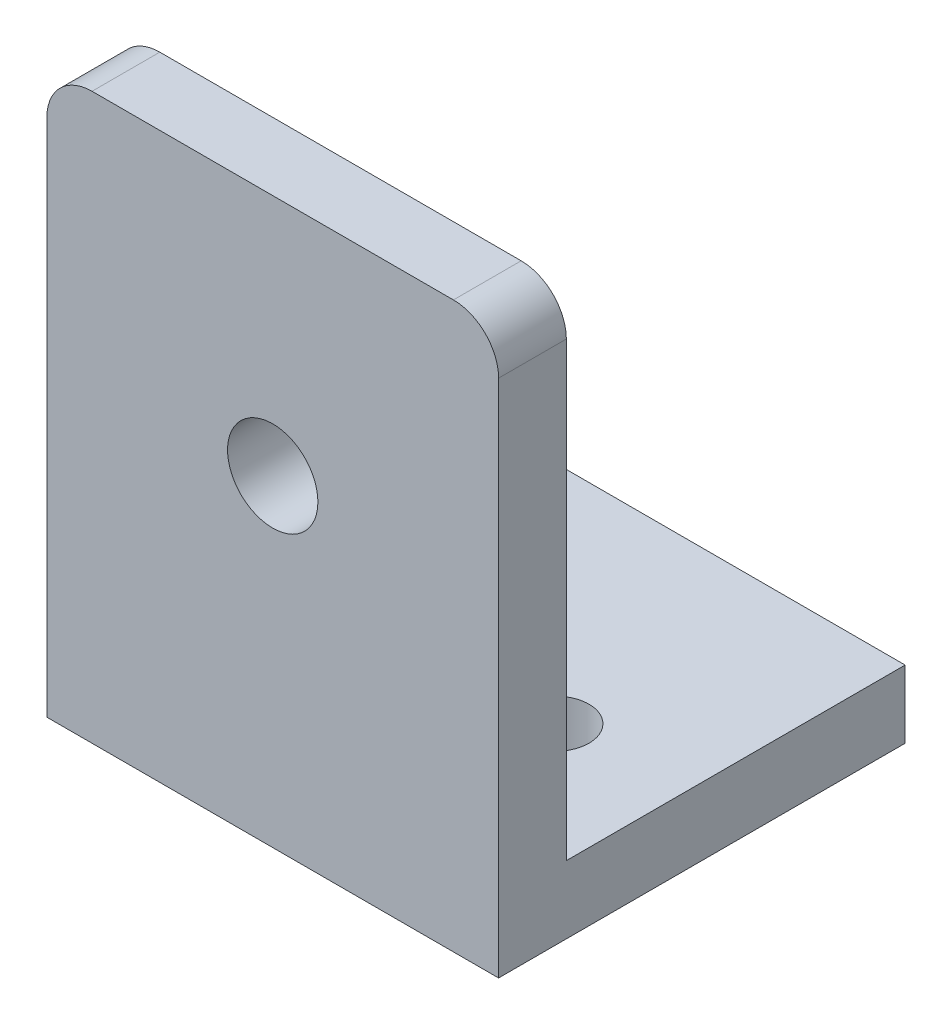
SolidWorks part; units mm, degrees
ref_plane "Front" through (0, 0, 0) normal (0, 0, 1) x (1, 0, 0)
ref_plane "Top" through (0, 0, 0) normal (0, 1, 0) x (1, 0, 0)
ref_plane "Right" through (0, 0, 0) normal (1, 0, 0) x (0, 0, -1)
sketch "草图1" plane through (0, 0, 0) normal (1, 0, 0) x (0, 0, -1)
  line L0 (0, 0) -> (0, 25)
  line L1 (0, 25) -> (3, 25)
  line L2 (3, 25) -> (3, 3)
  line L3 (3, 3) -> (18, 3)
  line L4 (18, 3) -> (18, 0)
  line L5 (18, 0) -> (0, 0)
  dimension "D1" = 25
  dimension "D2" = 3
  dimension "D3" = 22
  dimension "D4" = 15
extrude "凸台-拉伸1" add sketch "草图1" along normal blind 20
sketch "草图2" plane through (0, 3, 0) normal (0, 1, 0) x (1, 0, 0)
  line L0 (0, 8) -> (20, 8) construction
  line L1 (0, 18) -> (0, 3) construction
  line L2 (20, 18) -> (20, 3) construction
  line L3 (20, 0) -> (0, 0) construction
  circle A0 centre (5.5, 8) radius 1.5
  circle A1 centre (14.5, 8) radius 1.5
  dimension "D1" = 3
  dimension "D2" = 3
  dimension "D3" = 9
  dimension "D4" = 5.5
  dimension "D5" = 8
extrude "切除-拉伸1" cut sketch "草图2" against normal through all
fillet "圆角1" radius 2 2 edges at (0, 25, -1.5) (20, 25, -1.5)
sketch "草图3" plane through (0, 0, 0) normal (0, 0, 1) x (1, 0, 0)
  line L0 (10, 25) -> (10, 0) construction
  line L1 (18, 25) -> (2, 25) construction
  line L2 (20, 0) -> (0, 0) construction
  circle A0 centre (10, 14.25) radius 2
  dimension "D1" = 4
  dimension "D2" = 14.25
extrude "切除-拉伸2" cut sketch "草图3" against normal through all
